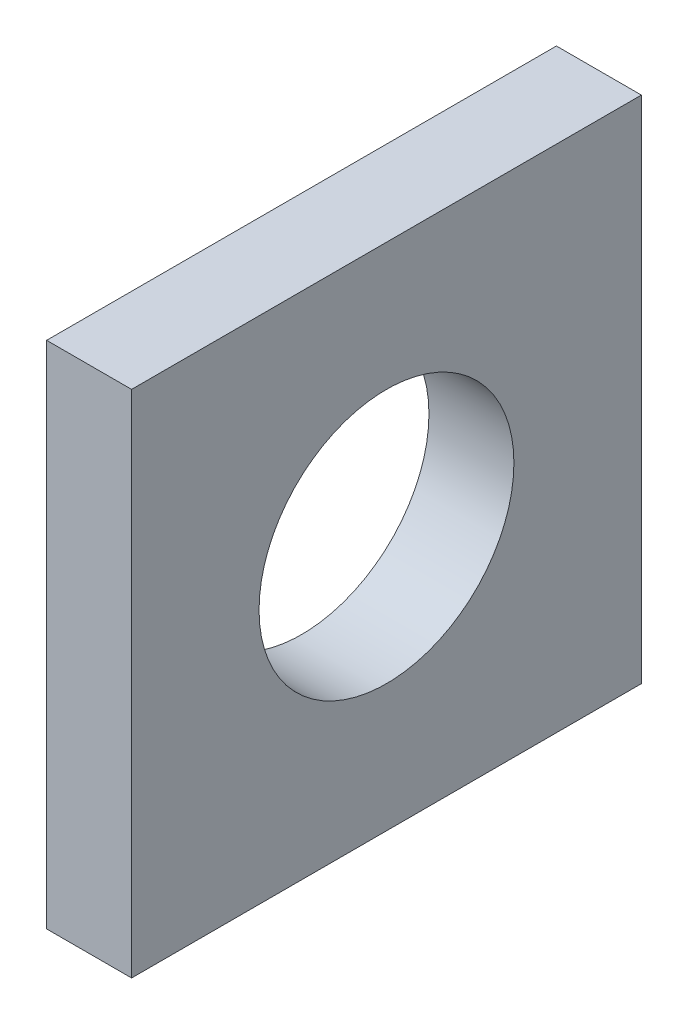
SolidWorks part; units mm, degrees
ref_plane "Front Plane" through (0, 0, 0) normal (0, 0, 1) x (1, 0, 0)
ref_plane "Top Plane" through (0, 0, 0) normal (0, 1, 0) x (1, 0, 0)
ref_plane "Right Plane" through (0, 0, 0) normal (1, 0, 0) x (0, 0, -1)
sketch "Sketch1" plane through (0, 0, 0) normal (1, 0, 0) x (0, 0, -1)
  line L1 (-9.525, -9.525) -> (9.525, -9.525)
  line L2 (-9.525, -9.525) -> (-9.525, 9.525)
  line L3 (-9.525, 9.525) -> (9.525, 9.525)
  line L4 (9.525, -9.525) -> (9.525, 9.525)
  line L5 (-9.525, -9.525) -> (9.525, 9.525) construction
  line L6 (-9.525, 9.525) -> (9.525, -9.525) construction
  circle A0 centre (0, 0) radius 4.7625
  point P0 (0, 0)
  dimension "D3" = 9.525
  dimension "D1" = 19.05
  dimension "D2" = 19.05
extrude "Boss-Extrude1" add sketch "Sketch1" along normal blind 3.175
